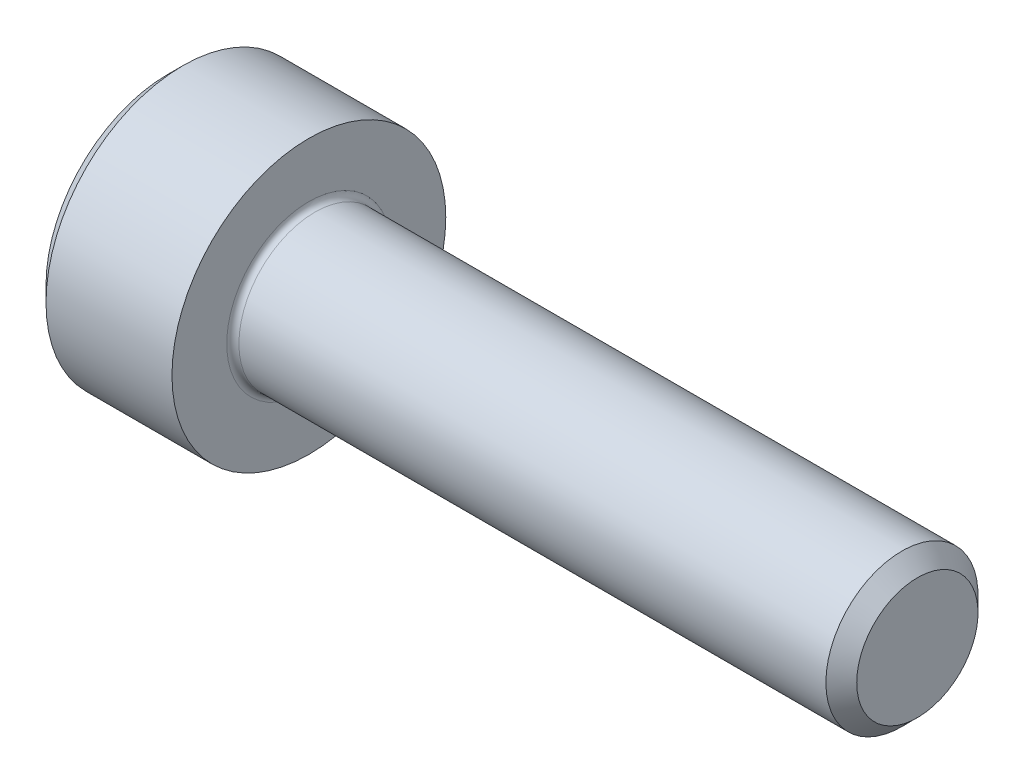
SolidWorks part; units mm, degrees
ref_plane "Plane1" through (0, 0, 0) normal (0, 0, 1) x (1, 0, 0)
ref_plane "Plane2" through (0, 0, 0) normal (0, 1, 0) x (1, 0, 0)
ref_plane "Plane3" through (0, 0, 0) normal (1, 0, 0) x (0, 0, -1)
sketch "BodySke" plane through (0, 0, 0) normal (0, 0, 1) x (1, 0, 0)
  line L0 (0, 0) -> (0, 2)
  line L1 (0.25, 2.25) -> (2.32, 2.25)
  line L2 (2.32, 2.25) -> (2.32, 1.25)
  line L3 (2.32, 1.25) -> (12.0665, 1.25)
  line L4 (12.32, 0.9965) -> (12.32, 0)
  line L5 (12.32, 0) -> (0, 0)
  line L6 (-31.75, 0) -> (127, 0) construction
  line L7 (0, 2) -> (0.25, 2.25)
  line L8 (12.32, 0.9965) -> (12.0665, 1.25)
  line L9 (0, -2) -> (0.25, -2.25) construction
  line L10 (12.32, -0.9965) -> (12.0665, -1.25) construction
  line L11 (2.77, 9.525) -> (2.77, 3.175) construction
  line L12 (2.32, 9.525) -> (2.32, 3.175) construction
  line L13 (-37.68, 9.525) -> (-37.68, 3.175) construction
  dimension "Diameter" = 2.5
  dimension "Head_ht" = 2.32
  dimension "Length" = 10
  dimension "Body_ch_ang" = 45
  dimension "Head_dia" = 4.5
  dimension "Head_ch_ang" = 45
  dimension "Minor_dia" = 1.993
  dimension "Advance" = 0.45
  dimension "Thread_nom" = 10
  dimension "Thread_length" = 50
  dimension "Head_ch_ht" = 0.25
revolve "Base-Revolve" add sketch "BodySke"
cosmetic thread "ThreadCosmetic"
fillet "Fillet1" radius 0.1 1 edges at (2.32, 0, 1.25)
sketch "Sketch2" plane through (0, 0, 0) normal (0, 0, 1) x (1, 0, 0)
  line L0 (0, 1.0225) -> (1.1, 1.0225)
  line L1 (1.1, 1.0225) -> (1.6903, 0)
  line L2 (-31.75, 0) -> (127, 0) construction
  line L3 (1.6903, 0) -> (0, 0)
  line L4 (0, 0) -> (0, 1.0225)
  line L5 (0, 2) -> (0, -2) construction
  line L6 (0, 0) -> (47.625, 0) construction
  line L7 (2.32, -2.25) -> (2.32, 2.25) construction
  dimension "D1" = 1.0225
  dimension "D2" = 60
  dimension "Wall_thickness" = 1.22
revolve "Hex-PreBroach" cut sketch "Sketch2" angle 360 about L6
sketch "Sketch3" plane through (0, 0, 0) normal (-1, 0, 0) x (0, 0.5, 0.866)
  line L0 (0.5903, 1.0225) -> (-0.5903, 1.0225)
  line L1 (-0.5903, 1.0225) -> (-1.1807, 0)
  line L2 (0.5903, 1.0225) -> (1.1807, 0)
  line L3 (0.5903, -1.0225) -> (1.1807, 0)
  line L4 (0.5903, -1.0225) -> (-0.5903, -1.0225)
  line L5 (-0.5903, -1.0225) -> (-1.1807, 0)
  dimension "D1" = 1.0225
  dimension "D2" = 1.0225
  dimension "Hex_size" = 2.045
extrude "Hex" cut sketch "Sketch3" against normal blind 1.1
sketch "Sketch4" plane through (0, 0, 0) normal (-1, 0, 0) x (0, 0, 1)
  line L0 (0, 0) -> (1.2446, 0)
  line L1 (0, 0) -> (6.1484, 3.5498) construction
  line L2 (0, 0) -> (0.6223, 1.0779)
  line L3 (1.0085, 0.2596) -> (1.19, 0.3644)
  line L4 (0.7291, 0.7436) -> (0.9106, 0.8484)
  arc A0 (1.0085, 0.2596) -> (0.7291, 0.7436) centre (0, 0) ccw
  arc A1 (1.2446, 0) -> (1.19, 0.3644) centre (0, 0) ccw
  arc A2 (0.6223, 1.0779) -> (0.9106, 0.8484) centre (0, 0) cw
  dimension "D1" = 30
  dimension "Spline_n_dim" = 2.0828
  dimension "Spline_m_dim" = 2.4892
  dimension "D2" = 60
  dimension "D3" = 0.2794
  dimension "Spline_p_dim" = 0.5588
extrude "Spline" [suppressed] cut sketch "Sketch4" against normal blind 1.1
pattern_circular "CirPattern1" [suppressed] count 6 every 60
sketch "Sketch5" plane through (0, 0, 0) normal (0, 0, 1) x (1, 0, 0)
  line L0 (-31.75, 0) -> (127, 0) construction
  line L2 (0, 2) -> (0, -2) construction
  circle A0 centre (0.1, 0) radius 0.005
  dimension "Drilled_hole_dia" = 0.01
  dimension "Drilled_hole_loc" = 0.1
extrude "Hole" [suppressed] cut sketch "Sketch5" against normal through all and the other way through all
pattern_circular "Drilled-4" [suppressed] count 2 every 60
pattern_circular "Drilled-6" [suppressed] count 3 every 60
sketch "ThdSchSke" plane through (0, 0, 0) normal (0, 0, 1) x (1, 0, 0)
  line L0 (2.77, -0.9965) -> (2.5925, -1.25)
  line L1 (2.77, -0.9965) -> (2.9475, -1.25)
  line L2 (2.9475, -1.25) -> (2.9475, -1.5625)
  line L3 (-3.175, 0) -> (5.1513, 0) construction
  line L5 (2.9475, -1.5625) -> (2.5925, -1.5625)
  line L6 (2.5925, -1.5625) -> (2.5925, -1.25)
  line L7 (0, 2) -> (0, -2) construction
  dimension "Thread_minor" = 1.993
  dimension "Diameter" = 2.5
  dimension "Start" = 2.77
  dimension "SideAngle" = 55
  dimension "VeeAngle" = 70
  dimension "Overcut" = 3.125
revolve "ThreadSchematic" [suppressed] cut sketch "ThdSchSke" angle 360 about L3
pattern_linear "ThdSchPat" [suppressed]
equation "\"D2@Sketch3\" = \"Hex_size@Sketch3\" / 2"
equation "\"D1@Sketch3\" = \"Hex_size@Sketch3\" / 2"
equation "\"D1@Sketch2\" = \"Hex_size@Sketch3\" / 2"
equation "\"D3@Sketch4\" = \"Spline_p_dim@Sketch4\" / 2"
equation "\"Thread_minor@ThreadCosmetic\"  =  \"Minor_dia@BodySke\""
equation "\"D2@CirPattern1\" = 360 / \"Num_teeth@CirPattern1\""
equation "\"Wall_thickness@Sketch2\" = \"Head_ht@BodySke\" - \"Key_eng@Hex\""
equation "\"Thread_length@ThreadCosmetic\" = ((sgn( (\"Length@BodySke\" - \"Advance@BodySke\" ) - \"Thread_nom@BodySke\" )-1)*( (\"Length@BodySke\" - \"Advance@BodySke\" ) - \"Thread_nom@BodySke\" ))/-2+ \"Thread_nom@BodySke\""
equation "\"Thread_minor@ThdSchSke\" = \"Minor_dia@BodySke\""
equation "\"Diameter@ThdSchSke\" = \"Diameter@BodySke\""
equation "\"Overcut@ThdSchSke\" = \"Diameter@BodySke\" * 1.25"
equation "\"Start@ThdSchSke\" = \"Head_ht@BodySke\" + \"Length@BodySke\" - \"Thread_length@ThreadCosmetic\"  '---Non-countersunk---"
equation "\"Num_threads@ThdSchPat\" = int( \"Thread_length@ThreadCosmetic\" / \"Advance@BodySke\" + 0.999 )  + 1"
equation "\"Advance@ThdSchPat\" = \"Thread_length@ThreadCosmetic\" /  (\"Num_threads@ThdSchPat\" - 1) 'relax it"
equation "\"Num_threads@ThdSchPat\" = \"Num_threads@ThdSchPat\" - sgn( \"Num_threads@ThdSchPat\" - 1) '---chamfered tips only---"
